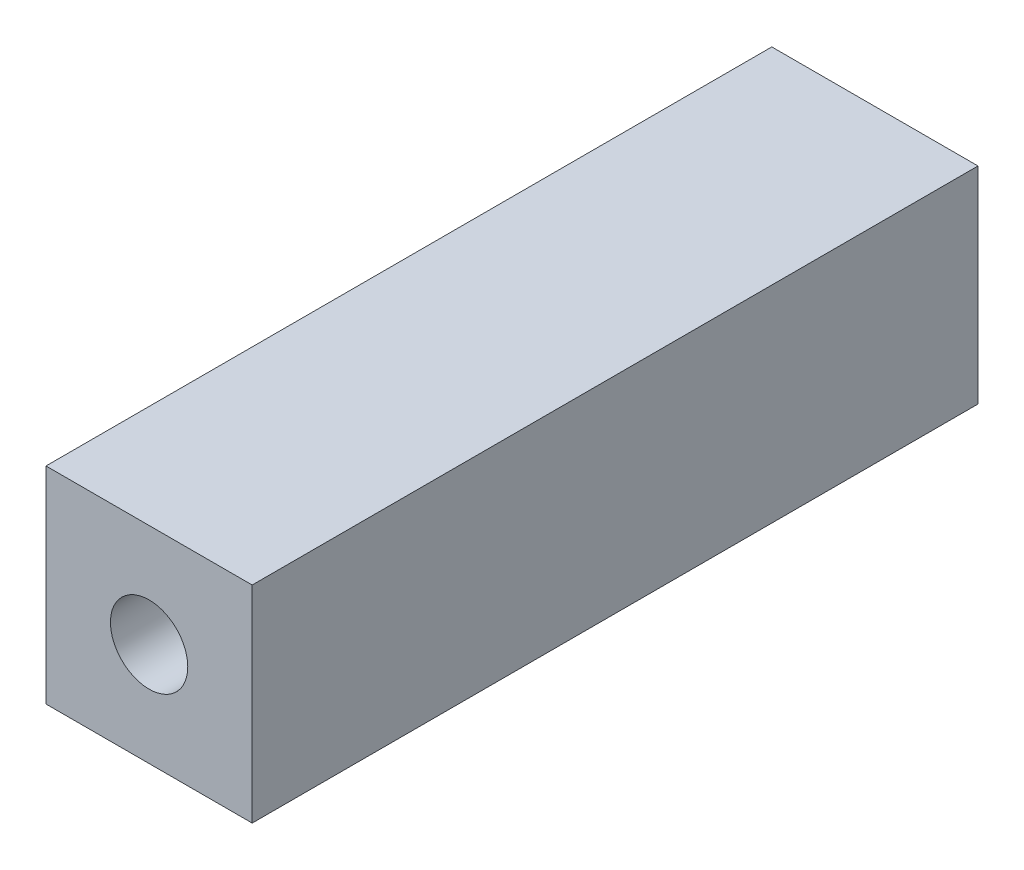
SolidWorks part; units mm, degrees
ref_plane "Front Plane" through (0, 0, 0) normal (0, 0, 1) x (1, 0, 0)
ref_plane "Top Plane" through (0, 0, 0) normal (0, 1, 0) x (1, 0, 0)
ref_plane "Right Plane" through (0, 0, 0) normal (1, 0, 0) x (0, 0, -1)
sketch "Sketch1" plane through (0, 0, 0) normal (0, 0, 1) x (1, 0, 0)
  line L1 (0, 0) -> (25.4, 0)
  line L2 (0, 0) -> (0, 25.4)
  line L3 (0, 25.4) -> (25.4, 25.4)
  line L4 (25.4, 0) -> (25.4, 25.4)
  dimension "D1" = 25.4
  dimension "D2" = 25.4
extrude "Boss-Extrude1" add sketch "Sketch1" along normal blind 89.408
sketch "Sketch2" plane through (0, 0, 89.408) normal (0, 0, 1) x (1, 0, 0)
  line L0 (0, 25.4) -> (0, 0) construction
  line L2 (25.4, 25.4) -> (0, 25.4) construction
  point P0 (12.7, 12.7)
  dimension "D1" = 12.7
  dimension "D2" = 12.7
sketch "Sketch3" plane through (0, 0, 0) normal (0, 0, -1) x (-1, 0, 0)
  line L0 (-25.4, 25.4) -> (0, 25.4) construction
  line L1 (0, 25.4) -> (0, 0) construction
  point P0 (-12.7, 12.7)
  dimension "D1" = 12.7
  dimension "D2" = 12.7
hole_wizard "3/8 (0.375) Diameter Hole1" positions "Sketch5" profile "Sketch4" hole size "3/8" standard "ANSI Inch"
sketch "Sketch5" plane through (0, 0, 0) normal (0, 0, -1) x (-1, 0, 0)
  point P0 (-12.7, 12.7)
sketch "Sketch4" plane through (12.7, 12.7, 0) normal (1, 0, 0) x (0, 1, 0)
  line L0 (0, 0) -> (0, 28.2616)
  line L1 (0, 28.2616) -> (4.7625, 25.4)
  line L2 (4.7625, 25.4) -> (4.7625, 0)
  line L5 (4.7625, 0) -> (0, 0)
  line L10 (0, 28.2616) -> (-4.7625, 25.4) construction
  line L11 (0, -6.35) -> (0, 107.95) construction
  dimension "Hole Dia." = 9.525
  dimension "Hole Depth" = 25.4
  dimension "Drill Angle" = 118
hole_wizard "3/8 (0.375) Diameter Hole2" positions "Sketch7" profile "Sketch6" hole size "3/8" standard "ANSI Inch"
sketch "Sketch7" plane through (0, 0, 89.408) normal (0, 0, 1) x (1, 0, 0)
  point P0 (12.7, 12.7)
sketch "Sketch6" plane through (12.7, 12.7, 89.408) normal (1, 0, 0) x (0, -1, 0)
  line L0 (0, 0) -> (0, 28.2616)
  line L1 (0, 28.2616) -> (4.7625, 25.4)
  line L2 (4.7625, 25.4) -> (4.7625, 0)
  line L5 (4.7625, 0) -> (0, 0)
  line L10 (0, 28.2616) -> (-4.7625, 25.4) construction
  line L11 (0, -6.35) -> (0, 107.95) construction
  dimension "Hole Dia." = 9.525
  dimension "Hole Depth" = 25.4
  dimension "Drill Angle" = 118
equation "\"D2@Sketch1\"=\"D1@Sketch1\""
